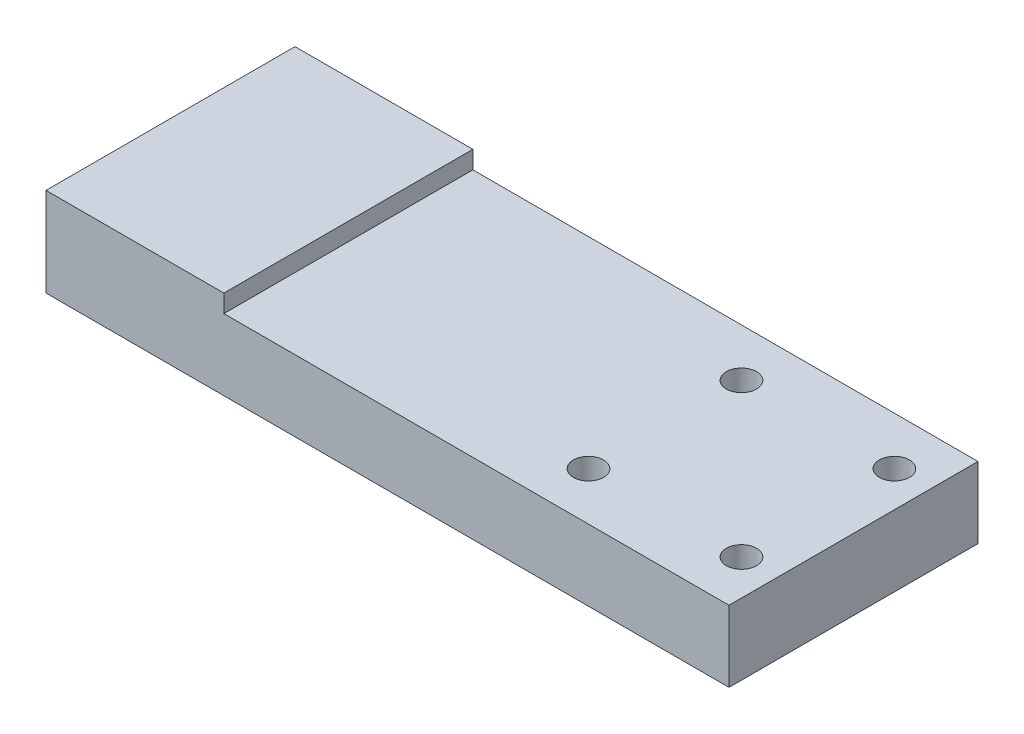
SolidWorks part; units mm, degrees
ref_plane "前视基准面" through (0, 0, 0) normal (0, 0, 1) x (1, 0, 0)
ref_plane "上视基准面" through (0, 0, 0) normal (0, 1, 0) x (1, 0, 0)
ref_plane "右视基准面" through (0, 0, 0) normal (1, 0, 0) x (0, 0, -1)
sketch "草图1" plane through (0, 0, 0) normal (0, 1, 0) x (1, 0, 0)
  line L1 (96, -35) -> (-96, -35)
  line L2 (96, -35) -> (96, 35)
  line L3 (96, 35) -> (-96, 35)
  line L4 (-96, -35) -> (-96, 35)
  line L5 (96, -35) -> (-96, 35) construction
  line L6 (96, 35) -> (-96, -35) construction
  point P0 (0, 0)
  dimension "D1" = 192
  dimension "D2" = 70
extrude "凸台-拉伸1" add sketch "草图1" along normal blind 25
sketch "草图2" plane through (0, 0, 0) normal (0, -1, 0) x (1, 0, 0)
  line L0 (0, 0) -> (50.8329, 0) construction
  line L1 (96, 35) -> (96, -35) construction
  circle A0 centre (86, 21.5) radius 4.25
  dimension "D3" = 8.5
  dimension "D1" = 10
  dimension "D2" = 43
extrude "切除-拉伸1" cut sketch "草图2" against normal up to next
pattern_linear "阵列(线性)1" count 2 spacing 43 along (-1, 0, 0) count 2 spacing 43 along (0, 0, -1) of "切除-拉伸1"
sketch "草图3" plane through (0, 25, 0) normal (0, 1, 0) x (1, 0, 0)
  line L0 (-46, 35) -> (-46, -35)
  line L1 (96, 35) -> (-96, 35) construction
  line L2 (-96, -35) -> (96, -35) construction
  line L3 (-46, -35) -> (96, -35)
  line L4 (96, -35) -> (96, 35)
  line L5 (96, 35) -> (-46, 35)
  line L6 (-96, 35) -> (-96, -35) construction
  dimension "D1" = 50
extrude "切除-拉伸2" cut sketch "草图3" against normal blind 5
